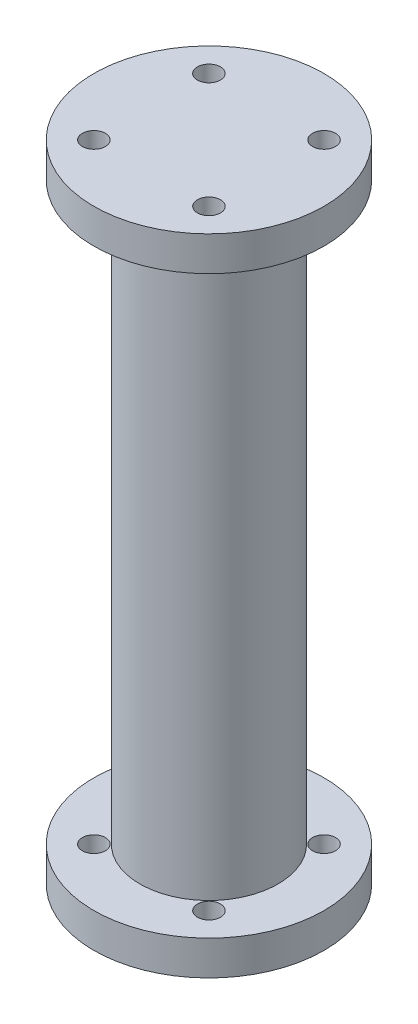
SolidWorks part; units mm, degrees
ref_plane "前视基准面" through (0, 0, 0) normal (0, 0, 1) x (1, 0, 0)
ref_plane "上视基准面" through (0, 0, 0) normal (0, 1, 0) x (1, 0, 0)
ref_plane "右视基准面" through (0, 0, 0) normal (1, 0, 0) x (0, 0, -1)
sketch "草图1" plane through (0, 0, 0) normal (0, 0, 1) x (1, 0, 0)
  line L0 (0, 25) -> (0, -25)
  line L1 (0, 25) -> (6, 25)
  line L3 (0, -25) -> (6, -25)
  line L4 (6, 25) -> (6, -25)
  line L5 (0, 0) -> (6, -25) construction
  line L6 (0, 0) -> (6, 25) construction
  point P0 (0, 0)
  dimension "D1" = 50
revolve "旋转1" add sketch "草图1" angle 360 about L0
sketch "草图2" plane through (0, 0, 0) normal (0, 0, 1) x (1, 0, 0)
  line L0 (6, 25) -> (-6, 25) construction
  line L1 (0, 25) -> (10, 25)
  line L2 (0, 25) -> (0, 28)
  line L3 (0, 28) -> (10, 28)
  line L4 (10, 25) -> (10, 28)
  line L5 (-25.2361, 0) -> (20.9778, 0) construction
  line L6 (10, -25) -> (10, -28)
  line L7 (0, -28) -> (10, -28)
  line L8 (0, -25) -> (0, -28)
  line L9 (0, -25) -> (10, -25)
  dimension "D1" = 3
  dimension "D2" = 10
revolve "旋转2" add sketch "草图2" angle 360 about L2
sketch "草图3" plane through (0, 28, 0) normal (0, 1, 0) x (1, 0, 0)
  line L0 (0, 11.576) -> (0, -12.4944) construction
  line L1 (-13.5467, 0) -> (12.7814, 0) construction
  circle A0 centre (-5, 5) radius 1
  circle A1 centre (5, 5) radius 1
  circle A2 centre (-5, -5) radius 1
  circle A3 centre (5, -5) radius 1
  dimension "D1" = 2
  dimension "D2" = 5
  dimension "D3" = 5
  dimension "D4" = 5
  dimension "D5" = 5
  dimension "D6" = 5
  dimension "D7" = 5
  dimension "D8" = 5
  dimension "D9" = 5
extrude "切除-拉伸1" cut sketch "草图3" against normal blind 5000
